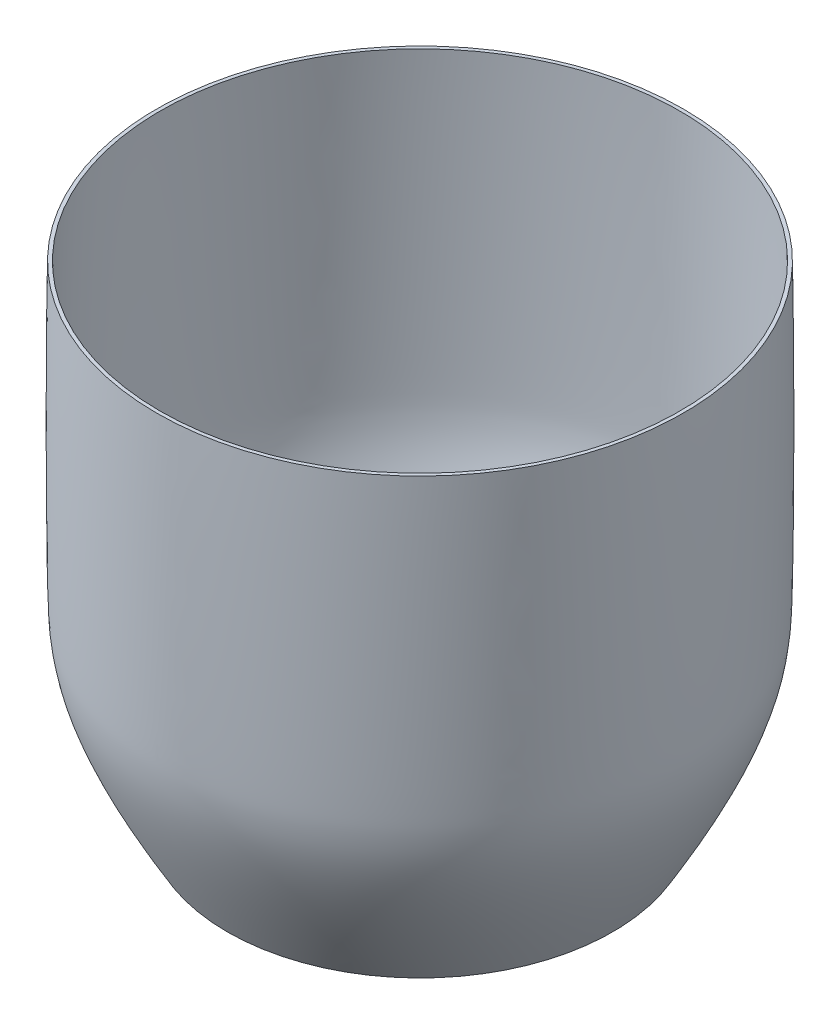
SolidWorks part; units mm, degrees
ref_plane "Front Plane" through (0, 0, 0) normal (0, 0, 1) x (1, 0, 0)
ref_plane "Top Plane" through (0, 0, 0) normal (0, 1, 0) x (1, 0, 0)
ref_plane "Right Plane" through (0, 0, 0) normal (1, 0, 0) x (0, 0, -1)
sketch "Sketch1" plane through (0, 0, 0) normal (0, 0, 1) x (1, 0, 0)
  line L0 (0, 0) -> (0, -225302.2188) construction
  line L1 (0, 0) -> (225302.2188, 0) construction
  line L2 (75, 358.9047) -> (75, -132.8896) construction
  line L3 (46, 279.115) -> (46, -70.3173) construction
  line L4 (-111.8818, -100) -> (191.8765, -100) construction
  line L5 (55, -60.3178) -> (55, -166.6222) construction
  line L6 (102.8246, -150) -> (32.2822, -150) construction
  line L7 (55, -150) -> (55.864, -150.5035)
  line L8 (45.0065, 0.1142) -> (46, 0)
  spline S0 degree 3 poles (46, 0) (50.9934, 43.4224) (74.4192, 29.0667) (75.8876, -30.1707) (75.6135, -93.03) (74.5222, -105.8967) (71.8537, -121.0755) (55, -150) knots 0 0 0 0 0.332423 0.386421 0.677937 0.742939 1 1 1 1
  spline S1 degree 1 poles (45.0065, 0.1142) (55.864, -150.5035) knots 0 0 1 1 construction
  spline S2 degree 3 poles (45.0065, 0.1142) (45.0648, 0.621) (45.1885, 1.6445) (45.4495, 3.6045) (45.8071, 5.9513) (46.2822, 8.5873) (46.9746, 11.8728) (47.9449, 15.5561) (49.2608, 19.3274) (50.7143, 22.4792) (52.8225, 25.8907) (55.7624, 28.7524) (59.7756, 29.9447) (63.7354, 28.856) (67.2723, 25.9932) (70.384, 21.6592) (72.9687, 16.0495) (74.9082, 9.3544) (76.0065, 1.7819) (76.3111, -6.5013) (76.4455, -15.8213) (76.5597, -26.0723) (76.6241, -36.8501) (76.6595, -51.4726) (76.6213, -65.7623) (76.5233, -78.3122) (76.4228, -86.504) (76.3193, -92.0173) (76.226, -95.4747) (76.127, -98.2132) (75.9803, -100.5168) (75.7264, -102.8046) (75.3257, -105.6918) (74.6213, -109.202) (73.4736, -113.4667) (71.7395, -118.5978) (69.6871, -123.6985) (67.6093, -128.3355) (65.8149, -132.1071) (63.7667, -136.1877) (61.833, -139.8595) (60.1418, -142.966) (58.7967, -145.3862) (57.3821, -147.8825) (56.3674, -149.6395) (55.864, -150.5035) knots 0 0 0 0 0.003906 0.007812 0.015625 0.023438 0.03125 0.046875 0.0625 0.078125 0.09375 0.125 0.15625 0.1875 0.21875 0.25 0.28125 0.3125 0.34375 0.375 0.40625 0.4375 0.46875 0.5 0.5625 0.59375 0.625 0.65625 0.671875 0.6875 0.71875 0.75 0.78125 0.8125 0.84375 0.875 0.90625 0.921875 0.9375 0.953125 0.96875 0.976562 0.984375 0.992188 1 1 1 1
  dimension "D1" = 75
  dimension "D2" = 46
  dimension "D3" = 100
  dimension "D4" = 150
  dimension "D5" = 55
  dimension "D6" = 1
revolve "Revolve1" add sketch "Sketch1" angle 360 about L0
sketch "Sketch2" plane through (0, 0, 0) normal (0, 0, 1) x (1, 0, 0)
  line L0 (-131.0148, -10) -> (151.3168, -10)
  line L1 (-131.0148, -10) -> (-131.0148, 125.8036)
  line L2 (-131.0148, 125.8036) -> (151.3168, 125.8036)
  line L3 (151.3168, 125.8036) -> (151.3168, -10)
  dimension "D1" = 10
extrude "Cut-Extrude1" cut sketch "Sketch2" against normal through all both and the other way through all
